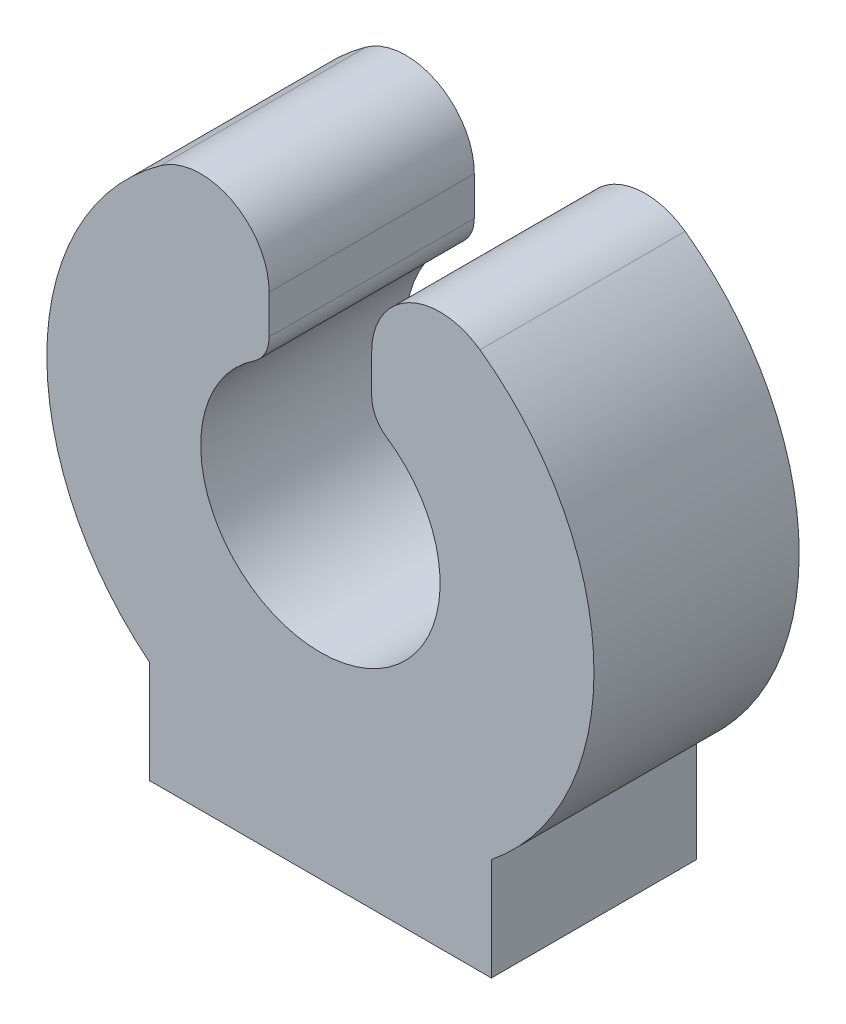
SolidWorks part; units mm, degrees
ref_plane "Front Plane" through (0, 0, 0) normal (0, 0, 1) x (1, 0, 0)
ref_plane "Top Plane" through (0, 0, 0) normal (0, 1, 0) x (1, 0, 0)
ref_plane "Right Plane" through (0, 0, 0) normal (1, 0, 0) x (0, 0, -1)
sketch "Sketch1" plane through (0, 0, 0) normal (0, 0, 1) x (1, 0, 0)
  line L0 (0, 3) -> (0, 0)
  line L1 (0, 0) -> (10, 0)
  line L2 (10, 0) -> (10, 3)
  arc A0 (10, 3) -> (0, 3) centre (5, 9.245) ccw
  circle A1 centre (5, 9.245) radius 3.5
  dimension "D1" = 10
  dimension "D3" = 8
  dimension "D4" = 7
  dimension "D2" = 3
extrude "Boss-Extrude1" add sketch "Sketch1" along normal blind 6
sketch "Sketch2" plane through (0, 0, 6) normal (0, 0, 1) x (1, 0, 0)
  line L0 (0, 0) -> (10, 0) construction
  line L1 (3.5, 18) -> (6.5, 18)
  line L2 (3.5, 18) -> (3.5, 12)
  line L3 (3.5, 12) -> (6.5, 12)
  line L4 (6.5, 18) -> (6.5, 12)
  line L5 (0, 3) -> (0, 0) construction
  dimension "D1" = 3
  dimension "D2" = 6
  dimension "D3" = 12
  dimension "D4" = 3.5
extrude "Cut-Extrude1" cut sketch "Sketch2" against normal through all
fillet "Fillet1" radius 2 2 edges at (6.5, 17.1031, 3) (3.5, 17.1031, 3)
fillet "Fillet2" radius 1 2 edges at (6.5, 12.4073, 3) (3.5, 12.4073, 3)
